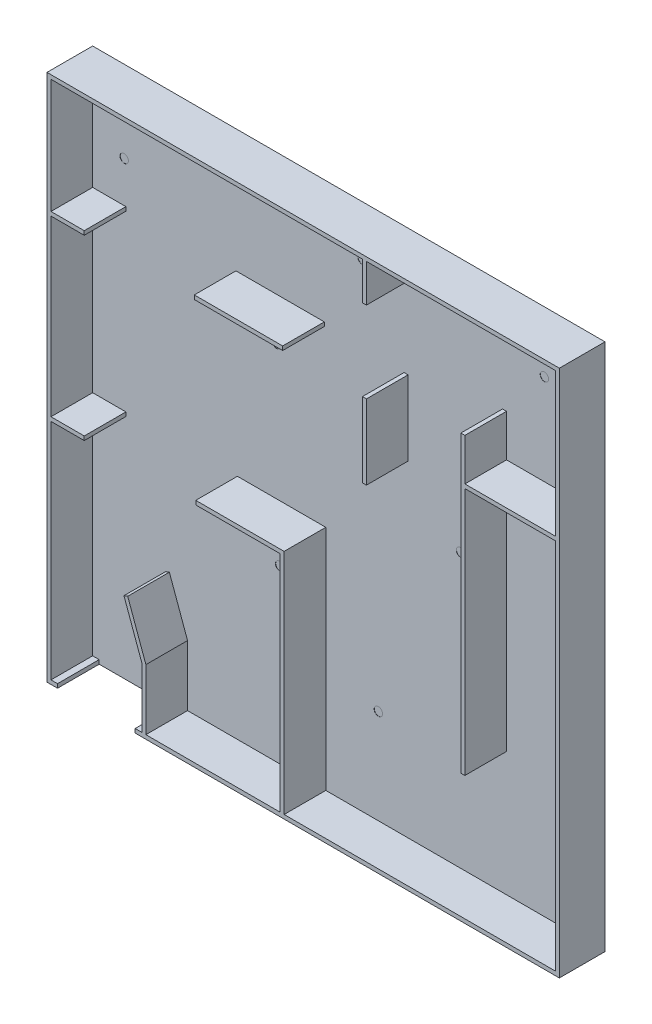
SolidWorks part; units mm, degrees
ref_plane "Plan de face" through (0, 0, 0) normal (0, 0, 1) x (1, 0, 0)
ref_plane "Plan de dessus" through (0, 0, 0) normal (0, 1, 0) x (1, 0, 0)
ref_plane "Plan de droite" through (0, 0, 0) normal (1, 0, 0) x (0, 0, -1)
sketch "Esquisse1" plane through (0, 0, 0) normal (0, 0, 1) x (1, 0, 0)
  line L1 (0, 0) -> (2435, 0)
  line L2 (0, 0) -> (0, 2510)
  line L3 (0, 2510) -> (2435, 2510)
  line L4 (2435, 0) -> (2435, 2510)
  dimension "D1" = 2510
  dimension "D2" = 2435
extrude "Extru.-Mince1" add sketch "Esquisse1" along normal blind 198 thin thin type one direction reverse wall 19
sketch "Esquisse2" plane through (0, 0, 0) normal (0, 0, -1) x (-1, 0, 0)
  line L1 (0, 2510) -> (-2435, 2510)
  line L2 (0, 2510) -> (0, 0)
  line L3 (0, 0) -> (-2435, 0)
  line L4 (-2435, 2510) -> (-2435, 0)
extrude "Boss.-Extru.1" add sketch "Esquisse2" along normal blind 19
sketch "Esquisse4" plane through (0, 0, 0) normal (0, 0, 1) x (1, 0, 0)
  line L0 (451, 19) -> (451, 304)
  line L1 (19, 19) -> (2416, 19) construction
  line L2 (451, 304) -> (365.7064, 539)
  line L3 (19, 2491) -> (19, 19) construction
  dimension "D1" = 432
  dimension "D2" = 285
  dimension "D3" = 250
  dimension "D4" = 520
extrude "Extru.-Mince3" add sketch "Esquisse4" along normal blind 198 thin
sketch "Esquisse5" plane through (0, 0, 0) normal (0, 0, 1) x (1, 0, 0)
  line L0 (1127, 1102) -> (1127, 19)
  line L4 (1127, 1102) -> (707, 1102)
  line L6 (470, 19) -> (2416, 19) construction
  line L7 (0, 2510) -> (0, 0) construction
  dimension "D1" = 1127
  dimension "D2" = 1083
  dimension "D3" = 420
extrude "Extru.-Mince4" add sketch "Esquisse5" along normal blind 198 thin
sketch "Esquisse6" plane through (0, 0, 0) normal (0, 0, 1) x (1, 0, 0)
  line L0 (19, 1928) -> (177, 1928)
  line L1 (19, 2491) -> (19, 19) construction
  line L3 (2435, 2510) -> (0, 2510) construction
  dimension "D1" = 582
  dimension "D3" = 158
extrude "Extru.-Mince5" add sketch "Esquisse6" along normal blind 198 thin thin type one direction reverse wall 19
sketch "Esquisse7" plane through (0, 0, 0) normal (0, 0, 1) x (1, 0, 0)
  line L0 (19, 1083) -> (177, 1083)
  line L3 (19, 1928) -> (19, 19) construction
  line L5 (2435, 2510) -> (0, 2510) construction
  dimension "D1" = 158
  dimension "D2" = 1427
extrude "Extru.-Mince6" add sketch "Esquisse7" along normal blind 198 thin thin type one direction reverse wall 19
sketch "Esquisse8" plane through (0, 0, 0) normal (0, -1, 0) x (1, 0, 0)
  line L0 (0, 198) -> (2435, 198) construction
  line L1 (50, 198) -> (419, 198)
  line L2 (50, 198) -> (50, 0)
  line L3 (50, 0) -> (419, 0)
  line L4 (419, 198) -> (419, 0)
  line L5 (0, 198) -> (0, -19) construction
  point P6 (0, 89.5)
  dimension "D1" = 198
  dimension "D2" = 369
  dimension "D3" = 50
extrude "Enlèv. mat.-Extru.1" cut sketch "Esquisse8" against normal blind 19
sketch "Esquisse9" plane through (0, 0, 0) normal (0, 0, 1) x (1, 0, 0)
  line L0 (1518, 2491) -> (1518, 2311)
  line L1 (2416, 2491) -> (19, 2491) construction
  line L3 (0, 2510) -> (0, 0) construction
  dimension "D1" = 180
  dimension "D2" = 1518
extrude "Extru.-Mince7" add sketch "Esquisse9" along normal blind 198 thin
sketch "Esquisse10" plane through (0, 0, 0) normal (0, 0, 1) x (1, 0, 0)
  line L0 (700, 1925) -> (1120, 1925)
  line L1 (2435, 2510) -> (0, 2510) construction
  line L2 (0, 0) -> (0, 2510) construction
  dimension "D1" = 420
  dimension "D2" = 585
  dimension "D3" = 1120
extrude "Extru.-Mince8" add sketch "Esquisse10" along normal blind 198 thin thin type one direction reverse wall 19
sketch "Esquisse11" plane through (0, 0, 0) normal (0, 0, 1) x (1, 0, 0)
  line L0 (1518, 1925) -> (1518, 1570)
  line L1 (2435, 2510) -> (0, 2510) construction
  line L4 (0, 2510) -> (0, 0) construction
  dimension "D1" = 355
  dimension "D2" = 940
  dimension "D3" = 1518
extrude "Extru.-Mince9" add sketch "Esquisse11" along normal blind 198 thin
sketch "Esquisse13" plane through (0, 0, 0) normal (0, 0, 1) x (1, 0, 0)
  line L0 (2416, 1809) -> (1967, 1809)
  line L1 (2416, 19) -> (2416, 2491) construction
  line L2 (1967, 1809) -> (1967, 609)
  line L3 (2435, 0) -> (2435, 2510) construction
  line L4 (419, 0) -> (2435, 0) construction
  dimension "D1" = 468
  dimension "D2" = 1809
  dimension "D3" = 1200
extrude "Extru.-Mince10" add sketch "Esquisse13" along normal blind 198 thin thin type one direction reverse wall 19
sketch "Esquisse14" plane through (0, 0, 0) normal (0, 0, 1) x (1, 0, 0)
  line L0 (1967, 1809) -> (1967, 2009)
  dimension "D1" = 200
extrude "Extru.-Mince11" add sketch "Esquisse14" along normal blind 198 thin
sketch "Esquisse15" plane through (0, 0, 0) normal (0, 0, 1) x (1, 0, 0)
  line L0 (700, 1925) -> (1120, 1925) construction
  point P0 (690.5, 1512.5)
  dimension "D1" = 9.5
  dimension "D2" = 412.5
sketch "Esquisse16" plane through (0, 0, 198) normal (0, 0, 1) x (1, 0, 0)
  line L0 (1499, 1925) -> (1499, 1570) construction
  line L1 (1499, 1925) -> (1518, 1925) construction
  line L2 (1518, 1925) -> (1518, 1570) construction
  line L3 (1518, 1570) -> (1499, 1570) construction
  point P0 (1508.5, 1930)
  point P3 (1508.5, 1925)
  point P6 (1508.5, 1569.99)
  point P9 (1508.5, 1570)
  dimension "D1" = 9.5
  dimension "D2" = 5
  dimension "D3" = 9.5
  dimension "D4" = 0.01
sketch "Esquisse17" plane through (0, 0, 0) normal (0, 0, 1) x (1, 0, 0)
  line L0 (2416, 1790) -> (1986, 1790) construction
  line L1 (2056, 1790) -> (2306, 1790)
  line L2 (2056, 1790) -> (2056, 1733.9716)
  line L3 (2056, 1733.9716) -> (2306, 1733.9716)
  line L4 (2306, 1790) -> (2306, 1733.9716)
  line L5 (1986, 1790) -> (1986, 609) construction
  dimension "D1" = 250
  dimension "D2" = 70
extrude "Boss.-Extru.2" add sketch "Esquisse17" along normal blind 10
sketch "Esquisse18" plane through (0, 0, 0) normal (0, 0, 1) x (1, 0, 0)
  line L0 (2416, 2491) -> (1518, 2491) construction
  line L1 (2416, 1809) -> (2416, 2491) construction
  line L2 (19, 2491) -> (19, 1947) construction
  line L3 (1499, 2491) -> (19, 2491) construction
  line L4 (1127, 19) -> (1127, 1102) construction
  line L5 (1127, 19) -> (2416, 19) construction
  line L6 (1967, 2009) -> (1967, 609) construction
  line L7 (1499, 2491) -> (19, 2491) construction
  line L8 (19, 1928) -> (19, 1102) construction
  line L9 (1108, 19) -> (1108, 1083) construction
  line L10 (1108, 1083) -> (707, 1083) construction
  line L11 (1499, 2491) -> (1499, 2311) construction
  circle A0 centre (2166, 2241) radius 20
  circle A1 centre (169, 2141) radius 20
  circle A2 centre (1377, 469) radius 20
  circle A3 centre (1767, 1319) radius 20
  circle A4 centre (894, 1741) radius 20
  circle A5 centre (908, 833) radius 20
  circle A6 centre (1299, 2291) radius 20
  dimension "D1" = 40
  dimension "D4" = 40
  dimension "D7" = 40
  dimension "D8" = 40
  dimension "D13" = 40
  dimension "D14" = 40
  dimension "D19" = 40
  dimension "D2" = 250
  dimension "D3" = 250
  dimension "D5" = 150
  dimension "D6" = 350
  dimension "D9" = 250
  dimension "D10" = 450
  dimension "D11" = 200
  dimension "D12" = 1300
  dimension "D15" = 750
  dimension "D16" = 875
  dimension "D17" = 200
  dimension "D18" = 250
  dimension "D20" = 200
  dimension "D21" = 200
extrude "Enlèv. mat.-Extru.2" cut sketch "Esquisse18" against normal blind 1
